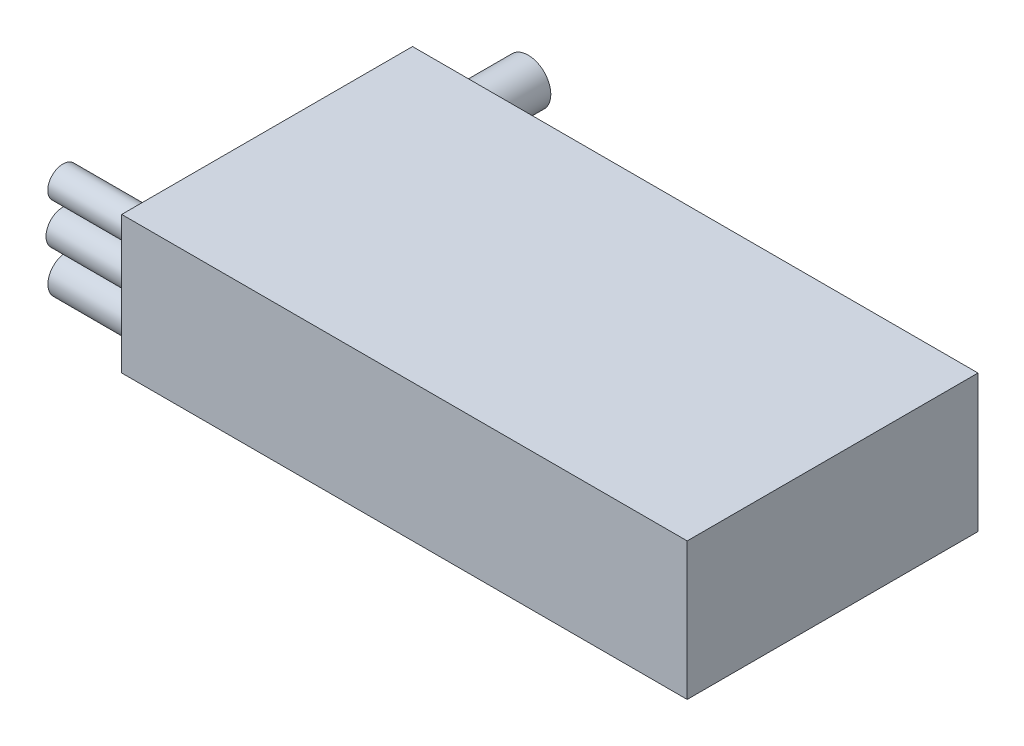
SolidWorks part; units mm, degrees
ref_plane "Спереди" through (0, 0, 0) normal (0, 0, 1) x (1, 0, 0)
ref_plane "Сверху" through (0, 0, 0) normal (0, 1, 0) x (1, 0, 0)
ref_plane "Справа" through (0, 0, 0) normal (1, 0, 0) x (0, 0, -1)
sketch "Sketch3" plane through (0, 0, 0) normal (0, 1, 0) x (1, 0, 0)
  line L1 (-35, 18) -> (35, 18)
  line L2 (-35, 18) -> (-35, -18)
  line L3 (-35, -18) -> (35, -18)
  line L4 (35, 18) -> (35, -18)
  line L5 (-35, 18) -> (35, -18) construction
  line L6 (-35, -18) -> (35, 18) construction
  point P0 (0, 0)
  dimension "D1" = 36
  dimension "D2" = 70
extrude "Boss-Extrude2" add sketch "Sketch3" along normal blind 17
sketch "Sketch4" plane through (-35, 0, 0) normal (-1, 0, 0) x (0, 0, 1)
  circle A0 centre (15.2749, 14.1664) radius 1.8806
  circle A1 centre (15.2749, 9.3322) radius 2.098
  circle A2 centre (14.8218, 4.0749) radius 2.319
extrude "Boss-Extrude3" add sketch "Sketch4" along normal blind 10
sketch "Sketch5" plane through (0, 0, -18) normal (0, 0, -1) x (-1, 0, 0)
  circle A0 centre (31.106, 3.8859) radius 2.6142
  circle A1 centre (30.6832, 10.4339) radius 2.8022
extrude "Boss-Extrude4" add sketch "Sketch5" along normal blind 10
